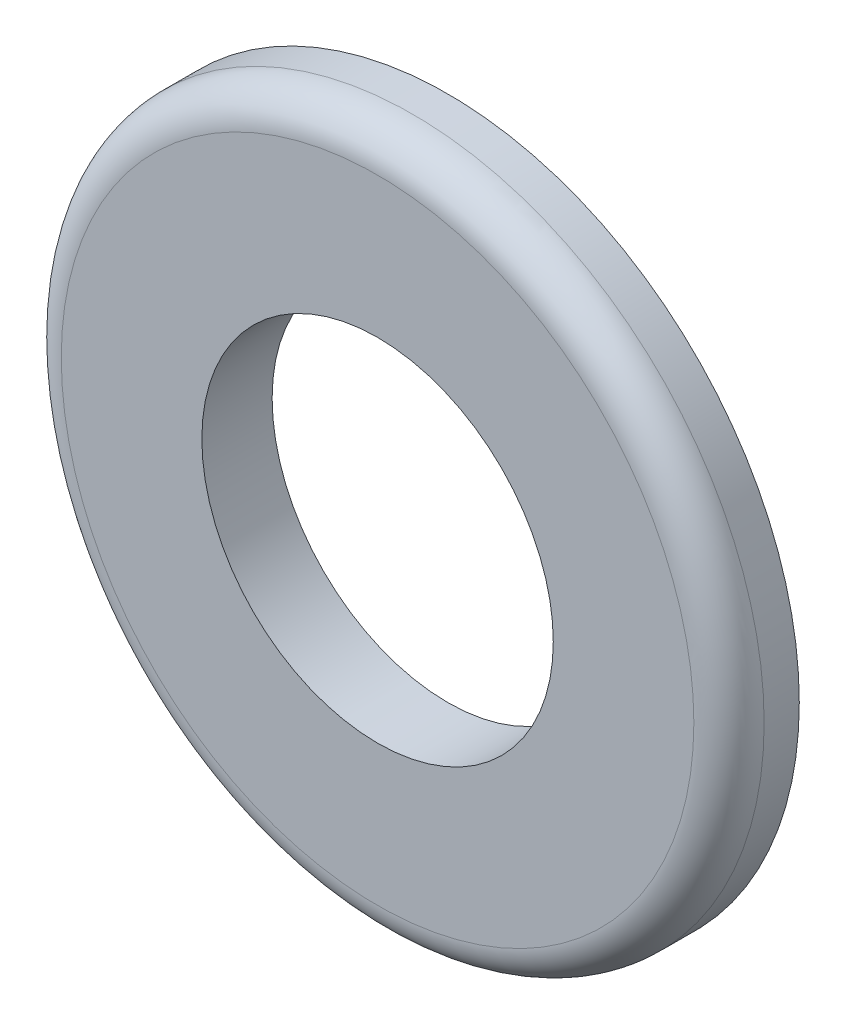
SolidWorks part; units mm, degrees
ref_plane "Alzado" through (0, 0, 0) normal (0, 0, 1) x (1, 0, 0)
ref_plane "Planta" through (0, 0, 0) normal (0, 1, 0) x (1, 0, 0)
ref_plane "Vista lateral" through (0, 0, 0) normal (1, 0, 0) x (0, 0, -1)
sketch "Croquis1" plane through (0, 0, 0) normal (0, 0, 1) x (1, 0, 0)
  circle A0 centre (0, 0) radius 2.5
  circle A1 centre (0, 0) radius 5
  dimension "D1" = 5
  dimension "D2" = 10
extrude "Saliente-Extruir1" add sketch "Croquis1" along normal blind 1 contours A0 | A1
fillet "Redondeo1" radius 0.5 1 edges at (5, 0, 1)
